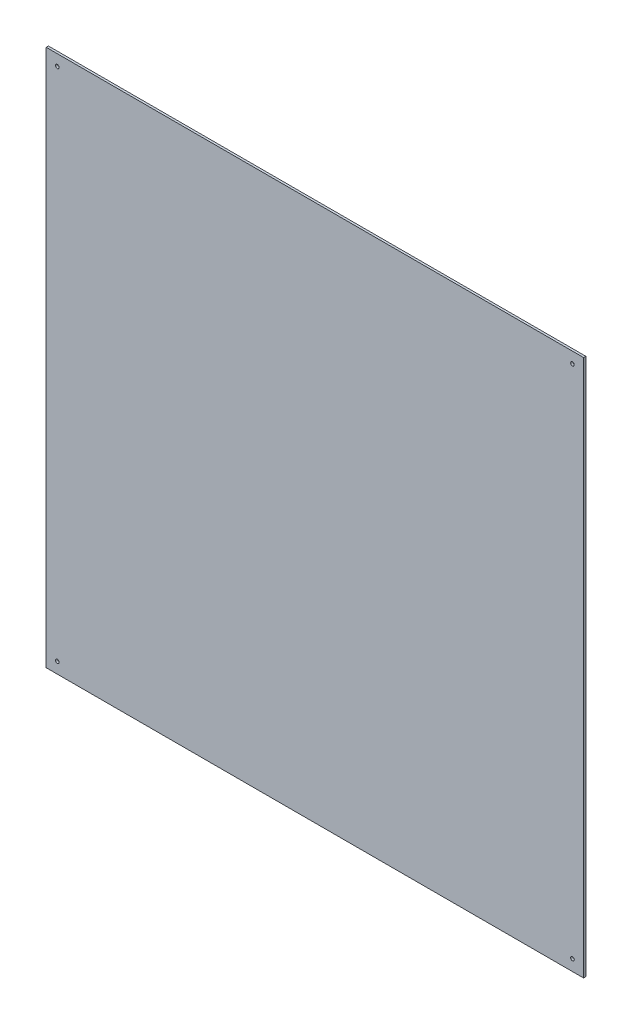
SolidWorks part; units mm, degrees
ref_plane "前视基准面" through (0, 0, 0) normal (0, 0, 1) x (1, 0, 0)
ref_plane "上视基准面" through (0, 0, 0) normal (0, 1, 0) x (1, 0, 0)
ref_plane "右视基准面" through (0, 0, 0) normal (1, 0, 0) x (0, 0, -1)
sketch "草图1" plane through (0, 0, 0) normal (0, 0, 1) x (1, 0, 0)
  line L0 (0, 70.3127) -> (0, -62.6576) construction
  line L1 (-95.9711, 0) -> (95.9711, 0) construction
  line L3 (-605, 605) -> (605, 605)
  line L4 (-605, 605) -> (-605, -605)
  line L5 (-605, -605) -> (605, -605)
  line L6 (605, 605) -> (605, -605)
extrude "凸台-拉伸1" add sketch "草图1" along normal blind 5
sketch "草图2" plane through (0, 0, 5) normal (0, 0, 1) x (1, 0, 0)
  line L0 (605, 605) -> (-605, 605) construction
  line L1 (605, -605) -> (605, 605) construction
  circle A0 centre (580, 580) radius 4.05
  dimension "D1" = 25
  dimension "D2" = 25
extrude "切除-拉伸1" cut sketch "草图2" against normal blind 5
pattern_linear "阵列(线性)1" count 2 spacing 1160 along (-1, 0, 0) count 2 spacing 1160 along (0, -1, 0) of "切除-拉伸1"
